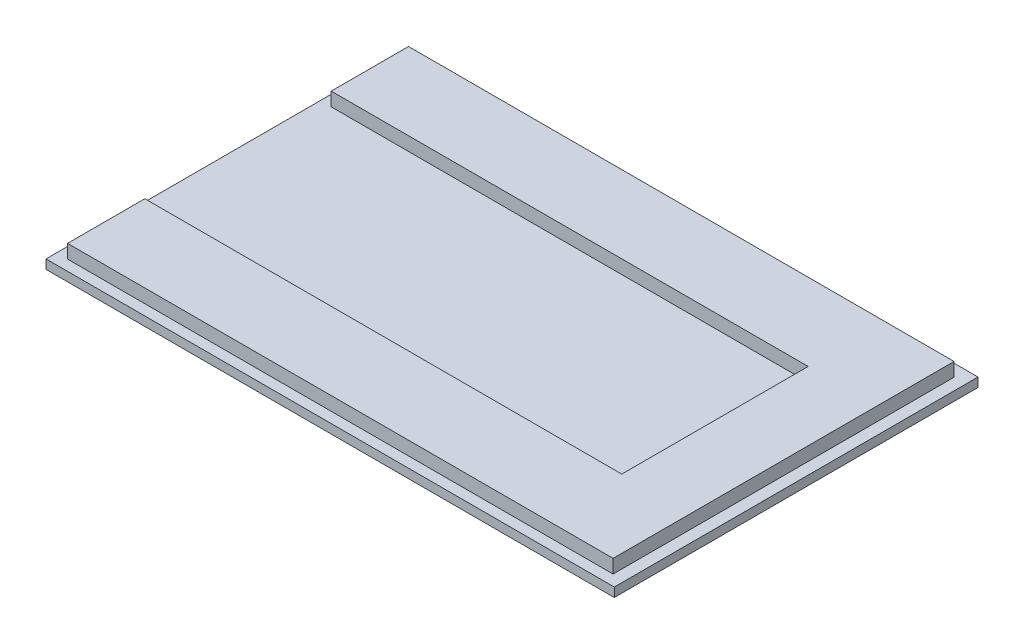
SolidWorks part; units mm, degrees
ref_plane "Front Plane" through (0, 0, 0) normal (0, 0, 1) x (1, 0, 0)
ref_plane "Top Plane" through (0, 0, 0) normal (0, 1, 0) x (1, 0, 0)
ref_plane "Right Plane" through (0, 0, 0) normal (1, 0, 0) x (0, 0, -1)
sketch "Sketch1" plane through (0, 0, 0) normal (0, 1, 0) x (1, 0, 0)
  line L1 (0, 0) -> (125, 0)
  line L2 (0, 0) -> (0, 80)
  line L3 (0, 80) -> (125, 80)
  line L4 (125, 0) -> (125, 80)
  dimension "D1" = 125
  dimension "D2" = 80
extrude "Boss-Extrude1" add sketch "Sketch1" along normal blind 2
sketch "Sketch3" plane through (0, 2, 0) normal (0, 1, 0) x (1, 0, 0)
  line L1 (2.4038, 77.336) -> (122.4038, 77.336)
  line L2 (2.4038, 77.336) -> (2.4038, 2.336)
  line L3 (2.4038, 2.336) -> (122.4038, 2.336)
  line L4 (122.4038, 77.336) -> (122.4038, 2.336)
  dimension "D1" = 120
  dimension "D2" = 75
extrude "Boss-Extrude2" add sketch "Sketch3" along normal blind 3
sketch "Sketch4" plane through (0, 5, 0) normal (0, 1, 0) x (1, 0, 0)
  line L0 (2.4038, 77.336) -> (2.4038, 2.336) construction
  line L1 (2.4038, 60.336) -> (107.3083, 60.336)
  line L2 (2.4038, 60.336) -> (2.4038, 19.336)
  line L3 (2.4038, 19.336) -> (107.3083, 19.336)
  line L4 (107.3083, 60.336) -> (107.3083, 19.336)
  line L5 (122.4038, 77.336) -> (2.4038, 77.336) construction
  line L6 (2.4038, 2.336) -> (122.4038, 2.336) construction
  dimension "D1" = 17
  dimension "D2" = 17
extrude "Cut-Extrude1" cut sketch "Sketch4" against normal blind 3
